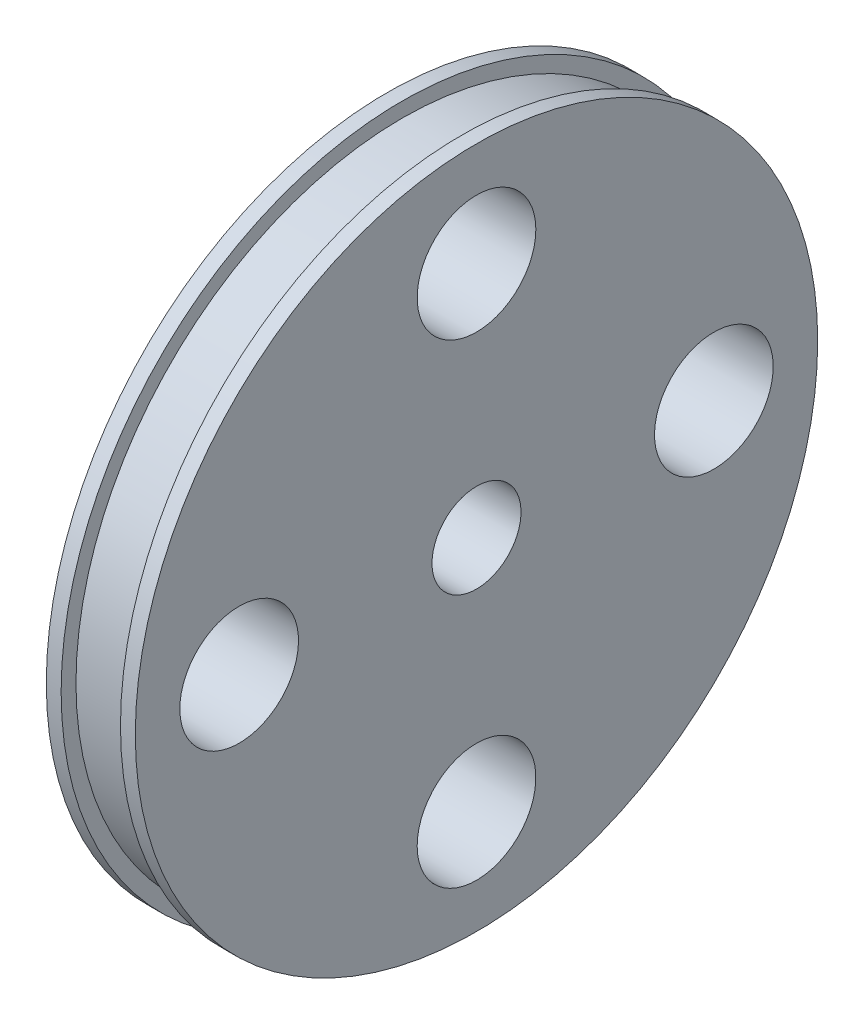
SolidWorks part; units mm, degrees
material "AISI Type 316L stainless steel"
ref_plane "Front Plane" through (0, 0, 0) normal (0, 0, 1) x (1, 0, 0)
ref_plane "Top Plane" through (0, 0, 0) normal (0, 1, 0) x (1, 0, 0)
ref_plane "Right Plane" through (0, 0, 0) normal (1, 0, 0) x (0, 0, -1)
sketch "Sketch1" plane through (0, 0, 0) normal (0, 0, 1) x (1, 0, 0)
  line L0 (-34.6098, -15) -> (62.6385, -15) construction
  line L1 (0, 0) -> (0, 100)
  line L2 (0, 100) -> (5, 100)
  line L3 (5, 100) -> (5, 95)
  line L4 (5, 95) -> (25, 95)
  line L5 (25, 95) -> (25, 100)
  line L6 (25, 100) -> (30, 100)
  line L7 (30, 100) -> (30, 0)
  line L8 (30, 0) -> (0, 0)
  dimension "D1" = 15
  dimension "D2" = 100
  dimension "D3" = 5
  dimension "D4" = 5
  dimension "D5" = 30
revolve "Revolve1" add sketch "Sketch1" angle 360 about L0
sketch "Sketch2" plane through (30, 0, 0) normal (1, 0, 0) x (0, 0, -1)
  circle A0 centre (0, 65) radius 20
  dimension "D2" = 40
  dimension "D1" = 65
extrude "Cut-Extrude1" cut sketch "Sketch2" against normal through all
pattern_circular "CirPattern1" count 4 over 360 about axis through (0, -15, 0) along (1, 0, 0) of "Cut-Extrude1"
